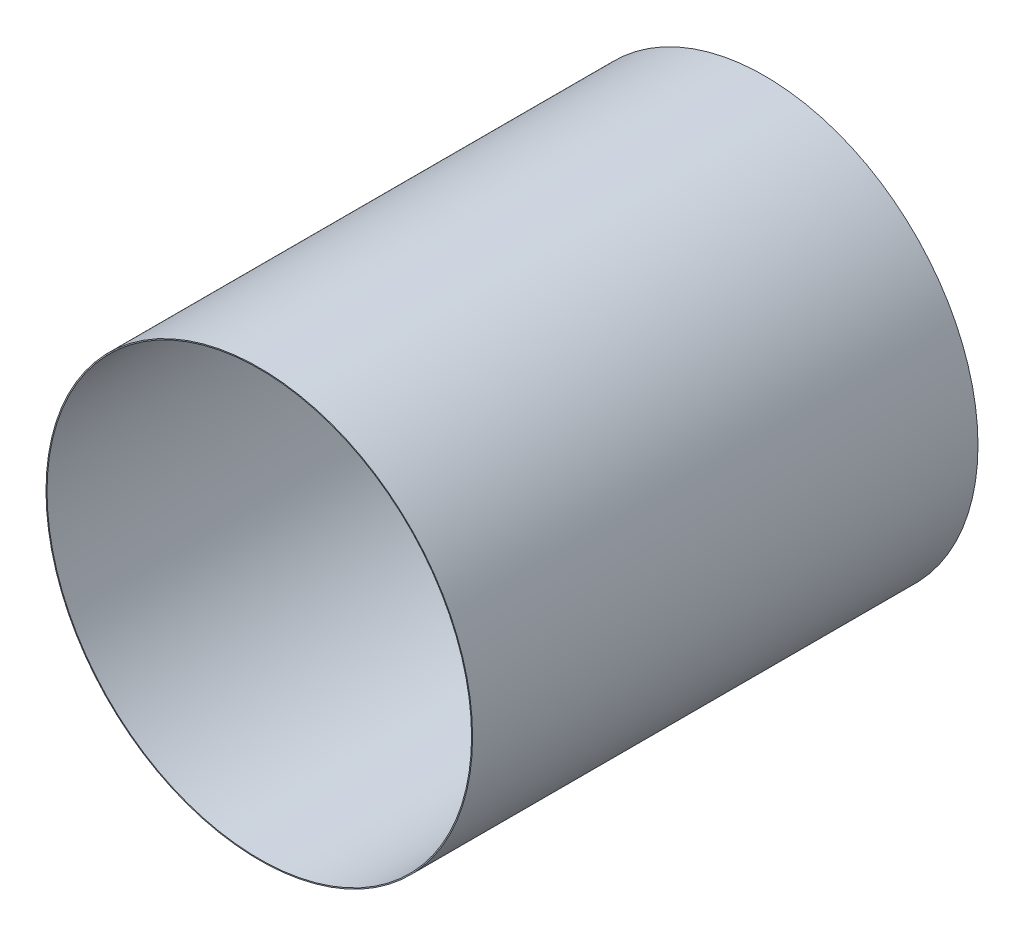
SolidWorks part; units mm, degrees
ref_plane "Front Plane" through (0, 0, 0) normal (0, 0, 1) x (1, 0, 0)
ref_plane "Top Plane" through (0, 0, 0) normal (0, 1, 0) x (1, 0, 0)
ref_plane "Right Plane" through (0, 0, 0) normal (1, 0, 0) x (0, 0, -1)
sketch "Sketch1" plane through (0, 0, 0) normal (0, 0, 1) x (1, 0, 0)
  circle A0 centre (0, 0) radius 10.55
  circle A1 centre (0, 0) radius 10.5
  dimension "D1" = 21
  dimension "D2" = 21.1
extrude "Boss-Extrude1" add sketch "Sketch1" along normal blind 25
